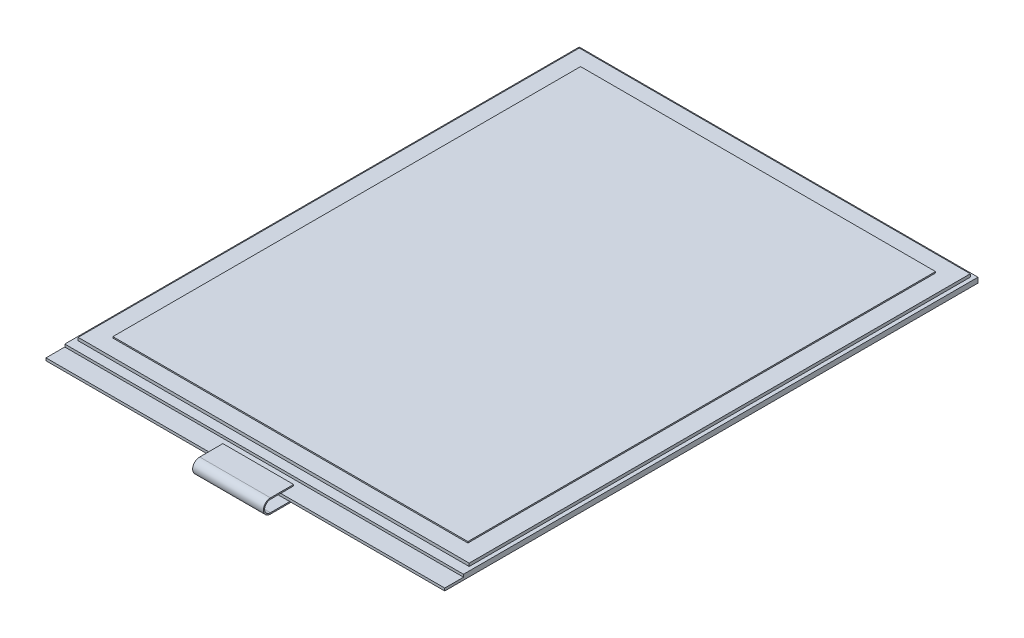
SolidWorks part; units mm, degrees
ref_plane "Front Plane" through (0, 0, 0) normal (0, 0, 1) x (1, 0, 0)
ref_plane "Top Plane" through (0, 0, 0) normal (0, 1, 0) x (1, 0, 0)
ref_plane "Right Plane" through (0, 0, 0) normal (1, 0, 0) x (0, 0, -1)
sketch "Sketch1" plane through (0, 0, 0) normal (0, 1, 0) x (1, 0, 0)
  line L1 (-15.5, 20.73) -> (15.5, 20.73)
  line L2 (-15.5, 20.73) -> (-15.5, -20.73)
  line L3 (-15.5, -20.73) -> (15.5, -20.73)
  line L4 (15.5, 20.73) -> (15.5, -20.73)
  line L5 (-15.5, 20.73) -> (15.5, -20.73) construction
  line L6 (-15.5, -20.73) -> (15.5, 20.73) construction
  point P0 (0, 0)
  dimension "D1" = 31
  dimension "D2" = 41.46
extrude "Boss-Extrude1" add sketch "Sketch1" along normal blind 0.2
sketch "Sketch2" plane through (0, 0.2, 0) normal (0, 1, 0) x (1, 0, 0)
  line L0 (15.5, -20.73) -> (15.5, 20.73) construction
  line L1 (-15.5, 20.73) -> (15.5, 20.73)
  line L2 (-15.5, 20.73) -> (-15.5, -19.27)
  line L3 (-15.5, -19.27) -> (15.5, -19.27)
  line L4 (15.5, 20.73) -> (15.5, -19.27)
  dimension "D1" = 40
extrude "Boss-Extrude2" add sketch "Sketch2" along normal blind 0.2
sketch "Sketch3" plane through (0, 0.4, 0) normal (0, 1, 0) x (1, 0, 0)
  line L0 (15.5, 20.73) -> (-15.5, 20.73) construction
  line L1 (-15.2, 20.43) -> (15.2, 20.43)
  line L2 (-15.2, 20.43) -> (-15.2, -18.53)
  line L3 (-15.2, -18.53) -> (15.2, -18.53)
  line L4 (15.2, 20.43) -> (15.2, -18.53)
  line L5 (-15.5, 20.73) -> (-15.5, -19.27) construction
  dimension "D1" = 30.4
  dimension "D2" = 38.96
  dimension "D3" = 0.3
  dimension "D4" = 0.3
extrude "Boss-Extrude3" add sketch "Sketch3" along normal blind 0.23
sketch "Sketch4" plane through (0, 0, 0) normal (0, -1, 0) x (1, 0, 0)
  line L0 (15.5, -20.73) -> (-15.5, -20.73) construction
  line L1 (-15.2, -20.43) -> (15.2, -20.43)
  line L2 (-15.2, -20.43) -> (-15.2, 18.53)
  line L3 (-15.2, 18.53) -> (15.2, 18.53)
  line L4 (15.2, -20.43) -> (15.2, 18.53)
  line L5 (-15.5, -20.73) -> (-15.5, 20.73) construction
  dimension "D1" = 30.4
  dimension "D2" = 38.96
  dimension "D3" = 0.3
  dimension "D4" = 0.3
extrude "Boss-Extrude4" add sketch "Sketch4" along normal blind 0.115
sketch "Sketch5" plane through (0, 0, 0) normal (1, 0, 0) x (0, 0, -1)
  line L0 (-20.73, 0.2) -> (-21.53, 0.2)
  line L1 (-21.53, 0.2) -> (-21.53, -0.7) construction
  line L2 (-21.53, -0.7) -> (-10.13, -0.7)
  line L3 (-10.13, -0.7) -> (-10.13, -0.8)
  line L4 (-10.13, -0.8) -> (-21.53, -0.8)
  line L5 (-21.53, 0.3) -> (-19.73, 0.3)
  line L6 (-19.73, 0.3) -> (-19.73, 0.2)
  line L7 (-19.27, 0.2) -> (-20.73, 0.2) construction
  line L8 (-19.73, 0.2) -> (-20.73, 0.2)
  arc A0 (-21.53, 0.2) -> (-21.53, -0.7) centre (-21.53, -0.25) ccw
  arc A1 (-21.53, 0.3) -> (-21.53, -0.8) centre (-21.53, -0.25) ccw
  dimension "D2" = 0.9
  dimension "D1" = 0.8
  dimension "D3" = 11.4
  dimension "D4" = 90
  dimension "D5" = 0.1
  dimension "D6" = 0.1
  dimension "D7" = 1.8
extrude "Boss-Extrude5" add sketch "Sketch5" along normal mid plane 5.5
sketch "Sketch7" plane through (0, 0.63, 0) normal (0, 1, 0) x (1, 0, 0)
  line L0 (0, 0) -> (0, 7.8471) construction
  line L1 (-15.2, -18.53) -> (15.2, -18.53) construction
  line L2 (-13.8, 19.13) -> (13.8, 19.13)
  line L3 (-13.8, 19.13) -> (-13.8, -17.23)
  line L4 (-13.8, -17.23) -> (13.8, -17.23)
  line L5 (13.8, 19.13) -> (13.8, -17.23)
  line L6 (-13.8, 19.13) -> (13.8, -17.23) construction
  line L7 (-13.8, -17.23) -> (13.8, 19.13) construction
  point P3 (0, 0.95)
  dimension "D1" = 36.36
  dimension "D2" = 27.6
  dimension "D3" = 1.3
extrude "Boss-Extrude6" add sketch "Sketch7" along normal blind 0.1
